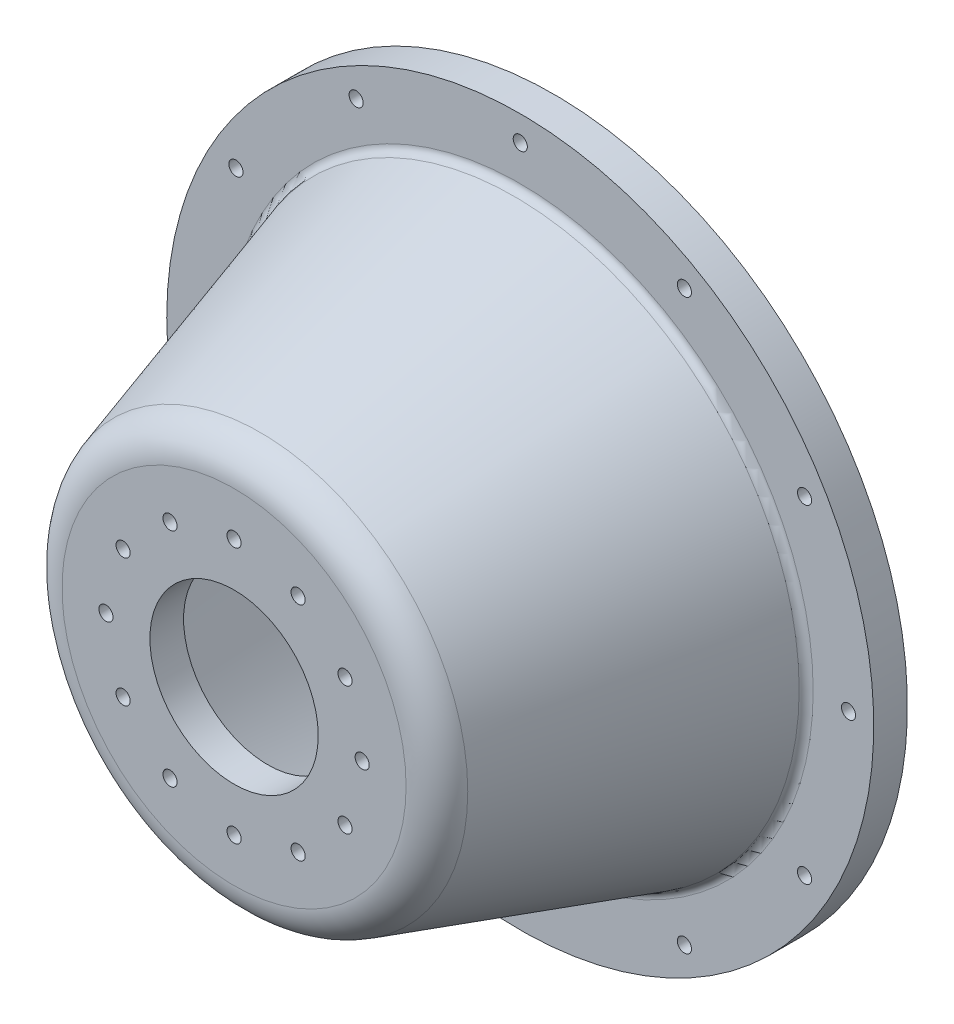
SolidWorks part; units mm, degrees
ref_plane "Front Plane" through (0, 0, 0) normal (0, 0, 1) x (1, 0, 0)
ref_plane "Top Plane" through (0, 0, 0) normal (0, 1, 0) x (1, 0, 0)
ref_plane "Right Plane" through (0, 0, 0) normal (1, 0, 0) x (0, 0, -1)
ref_plane "Plane1" through (0, 0, 0) normal (0, -1, 0) x (1, 0, 0)
sketch "Sketch1" plane through (0, 0, 0) normal (0, -1, 0) x (1, 0, 0)
  line L0 (210, 20) -> (0, 20)
  line L1 (0, 20) -> (0, 0)
  line L2 (0, 0) -> (210, 0)
  line L3 (210, 0) -> (210, 20)
  line L4 (0, 20) -> (0, 0) construction
revolve "Revolve1" add sketch "Sketch1" angle 360 about L4
sketch "Sketch2" plane through (0, 0, 20) normal (0, 0, 1) x (1, 0, 0)
  circle A0 centre (0, 0) radius 170.2968
extrude "Boss-Extrude1" add sketch "Sketch2" along normal blind 170 draft 16.95
sketch "Sketch3" plane through (0, 0, 0) normal (0, 1, 0) x (1, 0, 0)
  line L0 (155.4841, 0) -> (0, 0)
  line L1 (0, 0) -> (0, -190)
  line L2 (0, -190) -> (50, -190)
  line L3 (50, -190) -> (50, -170)
  line L4 (50, -170) -> (103.6717, -170)
  line L5 (103.6717, -170) -> (155.4841, 0)
  line L6 (0, 0) -> (0, -190) construction
revolve "Cut-Revolve1" cut sketch "Sketch3" angle 360 about L6
hole_wizard "Ø8.4 (8.4) Diameter Hole1" positions "Sketch5" profile "Sketch4" hole size "Ø8.4" standard "ANSI Metric"
sketch "Sketch5" plane through (0, 0, 20) normal (0, 0, 1) x (1, 0, 0)
  point P0 (0, 195)
  point P1 (97.5, 168.875)
  point P2 (168.875, 97.5)
  point P3 (195, 0)
  point P4 (168.875, -97.5)
  point P5 (97.5, -168.875)
  point P6 (0, -195)
  point P7 (-97.5, -168.875)
  point P8 (-168.875, -97.5)
  point P9 (-195, 0)
  point P10 (-168.875, 97.5)
  point P11 (-97.5, 168.875)
sketch "Sketch4" plane through (0, 195, 20) normal (1, 0, 0) x (0, -1, 0)
  line L0 (0, 0) -> (0, 20)
  line L1 (0, 20) -> (4.2, 20)
  line L2 (4.2, 20) -> (4.2, 0)
  line L5 (4.2, 0) -> (0, 0)
  line L11 (0, -6.35) -> (0, 107.95) construction
  dimension "Thru Hole Dia." = 8.4
  dimension "Thru Hole Depth" = 20
hole_wizard "Ø8.4 (8.4) Diameter Hole2" positions "Sketch7" profile "Sketch6" hole size "Ø8.4" standard "ANSI Metric"
sketch "Sketch7" plane through (0, 0, 170) normal (0, 0, -1) x (-1, 0, 0)
  point P0 (0, 76.0952)
  point P1 (38.0476, 65.9004)
  point P2 (65.9004, 38.0476)
  point P3 (76.0952, 0)
  point P4 (65.9004, -38.0476)
  point P5 (38.0476, -65.9004)
  point P6 (0, -76.0952)
  point P7 (-38.0476, -65.9004)
  point P8 (-65.9004, -38.0476)
  point P9 (-76.0952, 0)
  point P10 (-65.9004, 38.0476)
  point P11 (-38.0476, 65.9004)
sketch "Sketch6" plane through (0, 76.0952, 170) normal (1, 0, 0) x (0, 1, 0)
  line L0 (0, 0) -> (0, 20)
  line L1 (0, 20) -> (4.2, 20)
  line L2 (4.2, 20) -> (4.2, 0)
  line L5 (4.2, 0) -> (0, 0)
  line L11 (0, -6.35) -> (0, 107.95) construction
  dimension "Thru Hole Dia." = 8.4
  dimension "Thru Hole Depth" = 20
fillet "Fillet1" radius 2 1 edges at (103.6717, 0, 170)
fillet "Fillet2" radius 5 1 edges at (170.2968, 0, 20)
fillet "Fillet3" radius 22 1 edges at (118.4844, 0, 190)
fillet "Fillet4" radius 25 1 edges at (155.4841, 0, 0)
